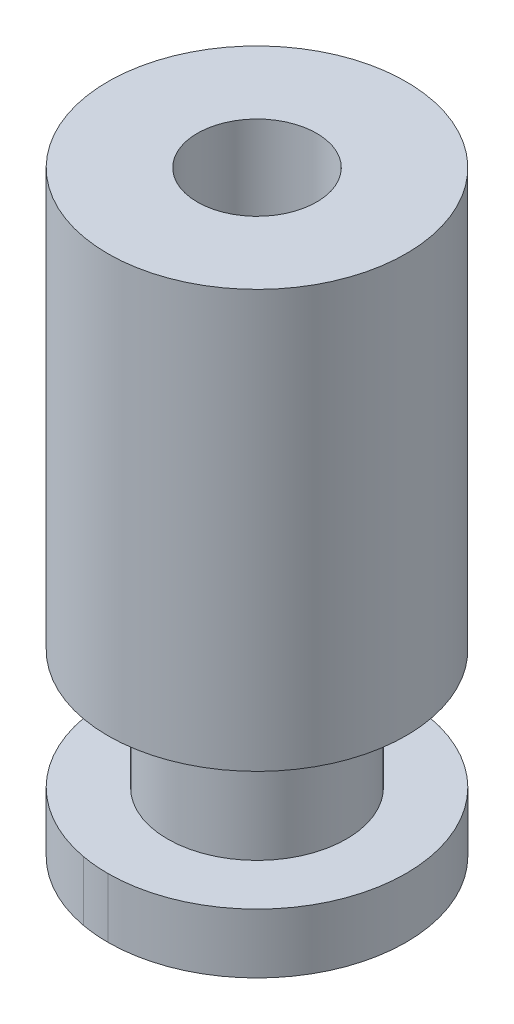
SolidWorks part; units mm, degrees
ref_plane "Front Plane" through (0, 0, 0) normal (0, 0, 1) x (1, 0, 0)
ref_plane "Top Plane" through (0, 0, 0) normal (0, 1, 0) x (1, 0, 0)
ref_plane "Right Plane" through (0, 0, 0) normal (1, 0, 0) x (0, 0, -1)
sketch "Sketch1" plane through (0, 0, 0) normal (0, 1, 0) x (1, 0, 0)
  circle A0 centre (0, 0) radius 12.5
  dimension "D1" = 25
extrude "Boss-Extrude1" add sketch "Sketch1" along normal blind 50
sketch "Sketch2" plane through (0, 50, 0) normal (0, 1, 0) x (1, 0, 0)
  circle A0 centre (0, 0) radius 5
  dimension "D1" = 10
extrude "Cut-Extrude1" cut sketch "Sketch2" against normal blind 20
sketch "Sketch3" plane through (0, 0, 0) normal (1, 0, 0) x (0, 0, -1)
  line L0 (0, 58.2664) -> (0, -7.1592) construction
  line L1 (12.5, 15) -> (7.5, 15)
  line L2 (12.5, 0) -> (12.5, 50) construction
  line L3 (7.5, 15) -> (7.5, 5)
  line L4 (7.5, 5) -> (12.5, 5)
  line L5 (12.5, 5) -> (12.5, 15)
  line L6 (-12.5, 0) -> (12.5, 0) construction
  dimension "D1" = 5
  dimension "D2" = 15
  dimension "D3" = 5
revolve "Cut-Revolve1" cut sketch "Sketch3" angle 360 about L0
sketch "Sketch4" plane through (0, 0, 0) normal (0, 0, 1) x (1, 0, 0)
  line L0 (12.5, 5) -> (-12.5, 5) construction
  line L1 (0, 0) -> (-2.2717, 0)
  line L2 (0, 0) -> (0, 5)
  line L3 (0, 5) -> (-2.2717, 5)
  line L4 (-2.2717, 0) -> (-2.2717, 5)
split line "Split Line1"
